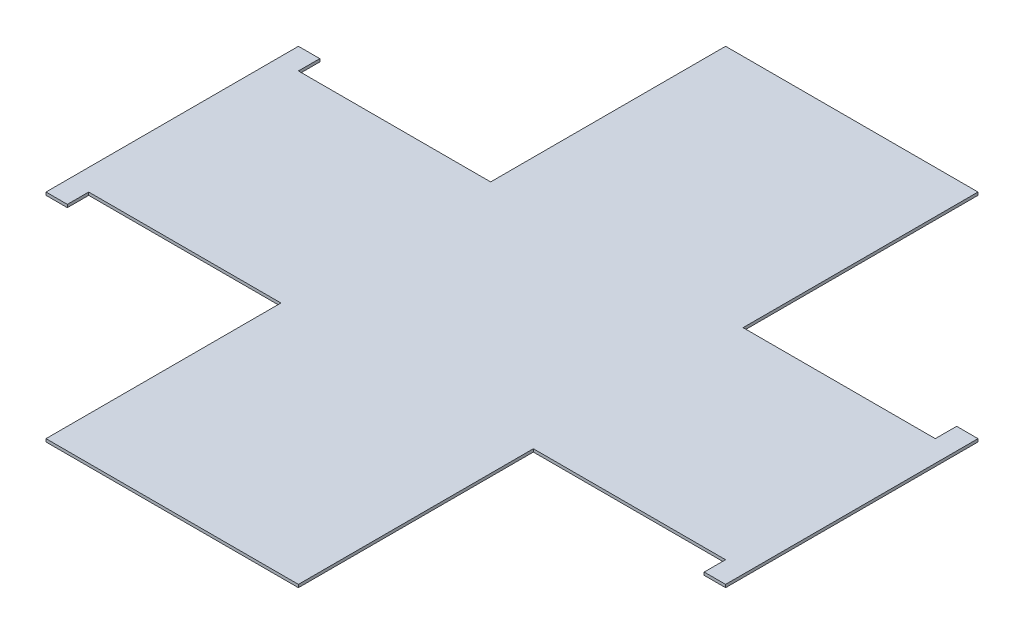
SolidWorks part; units mm, degrees
ref_plane "Front Plane" through (0, 0, 0) normal (0, 0, 1) x (1, 0, 0)
ref_plane "Top Plane" through (0, 0, 0) normal (0, 1, 0) x (1, 0, 0)
ref_plane "Right Plane" through (0, 0, 0) normal (1, 0, 0) x (0, 0, -1)
sketch "Sketch1" plane through (0, 0, 0) normal (0, 1, 0) x (1, 0, 0)
  line L0 (-350, -130) -> (-328, -130)
  line L1 (-130, -350) -> (130, -350)
  line L2 (-350, -130) -> (-350, 130)
  line L3 (-130, 350) -> (130, 350)
  line L4 (350, -130) -> (350, 130)
  line L7 (-350, 350) -> (-130, 350) construction
  line L8 (-350, 350) -> (-350, 130) construction
  line L9 (-350, 130) -> (-328, 130)
  line L10 (-130, 350) -> (-130, 130)
  line L11 (-350, 350) -> (-130, 130) construction
  line L12 (-350, 130) -> (-130, 350) construction
  line L13 (-350, -130) -> (-350, -350) construction
  line L14 (-350, -350) -> (-130, -350) construction
  line L15 (-130, -130) -> (-130, -350)
  line L16 (-350, -130) -> (-130, -350) construction
  line L17 (-350, -350) -> (-130, -130) construction
  line L18 (130, 350) -> (350, 350) construction
  line L19 (130, 350) -> (130, 130)
  line L20 (328, 130) -> (350, 130)
  line L21 (350, 350) -> (350, 130) construction
  line L22 (130, 350) -> (350, 130) construction
  line L23 (130, 130) -> (350, 350) construction
  line L24 (328, -130) -> (350, -130)
  line L25 (130, -130) -> (130, -350)
  line L26 (130, -350) -> (350, -350) construction
  line L27 (350, -130) -> (350, -350) construction
  line L28 (130, -130) -> (350, -350) construction
  line L29 (130, -350) -> (350, -130) construction
  line L30 (-328, -108) -> (-130, -108)
  line L31 (-328, 130) -> (-130, 130) construction
  line L32 (-328, 130) -> (-328, 108)
  line L33 (-328, 108) -> (-130, 108)
  line L34 (-130, 130) -> (-130, 108)
  line L35 (-328, 130) -> (-130, 108) construction
  line L36 (-328, 108) -> (-130, 130) construction
  line L37 (-328, -108) -> (-328, -130)
  line L38 (-328, -130) -> (-130, -130) construction
  line L39 (-130, -108) -> (-130, -130)
  line L40 (-328, -108) -> (-130, -130) construction
  line L41 (-328, -130) -> (-130, -108) construction
  line L42 (130, 130) -> (328, 130) construction
  line L43 (130, 130) -> (130, 108)
  line L44 (130, 108) -> (328, 108)
  line L45 (328, 130) -> (328, 108)
  line L46 (130, 130) -> (328, 108) construction
  line L47 (130, 108) -> (328, 130) construction
  line L48 (130, -108) -> (328, -108)
  line L49 (130, -108) -> (130, -130)
  line L50 (130, -130) -> (328, -130) construction
  line L51 (328, -108) -> (328, -130)
  line L52 (130, -108) -> (328, -130) construction
  line L53 (130, -130) -> (328, -108) construction
  line L54 (-130, 350) -> (130, -350) construction
  point P0 (0, 0)
  point P1 (0, 0)
  point P10 (-240, 240)
  point P15 (-240, -240)
  point P20 (240, 240)
  point P25 (240, -240)
  point P30 (-229, 119)
  point P35 (-229, -119)
  point P40 (229, 119)
  point P45 (229, -119)
  dimension "D3" = 220
  dimension "D4" = 220
  dimension "D5" = 220
  dimension "D6" = 220
  dimension "D7" = 220
  dimension "D8" = 220
  dimension "D9" = 220
  dimension "D10" = 220
  dimension "D11" = 22
  dimension "D12" = 198
  dimension "D13" = 22
  dimension "D14" = 198
  dimension "D15" = 22
  dimension "D16" = 198
  dimension "D17" = 22
  dimension "D18" = 198
extrude "Boss-Extrude1" add sketch "Sketch1" along normal blind 3
